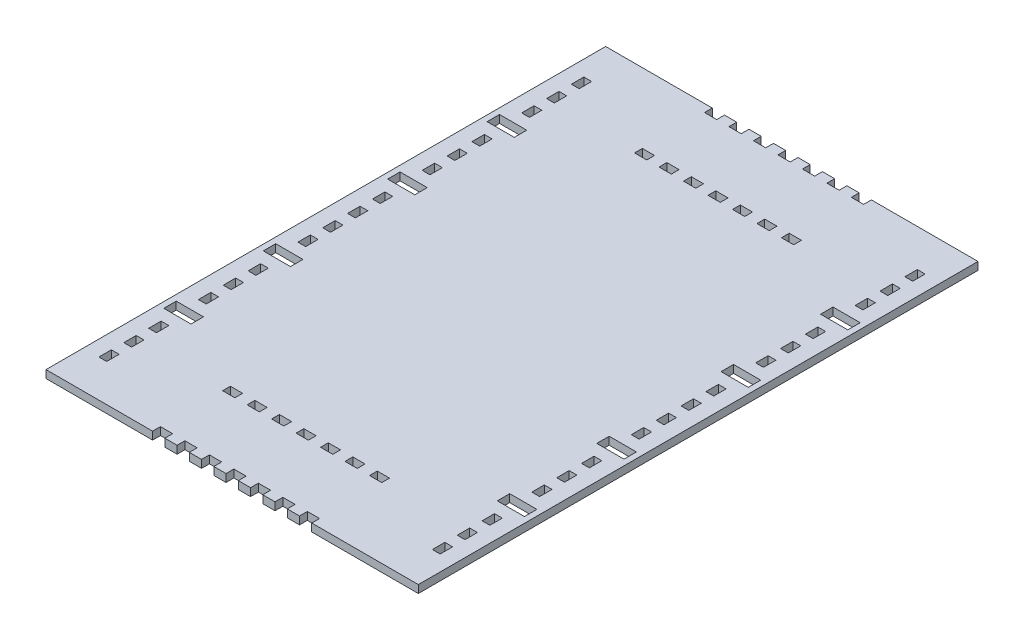
SolidWorks part; units mm, degrees
ref_plane "Front Plane" through (0, 0, 0) normal (0, 0, 1) x (1, 0, 0)
ref_plane "Top Plane" through (0, 0, 0) normal (0, 1, 0) x (1, 0, 0)
ref_plane "Right Plane" through (0, 0, 0) normal (1, 0, 0) x (0, 0, -1)
sketch "Sketch2" plane through (0, 0, 0) normal (0, 1, 0) x (1, 0, 0)
  line L0 (11.1148, -172.4341) -> (11.1148, -125.5432) construction
  line L1 (-64.9264, -175.6306) -> (-21.3852, -175.6306)
  line L2 (-64.9264, -175.6306) -> (-64.9264, -129.8959)
  line L3 (-64.9264, 52.9694) -> (-21.3852, 52.9694)
  line L4 (87.1561, -175.6306) -> (87.1561, -129.8959)
  line L5 (-58.5764, -160.3691) -> (-55.4014, -160.3691)
  line L6 (-58.5764, -160.3691) -> (-58.5764, -155.2891)
  line L7 (-58.5764, -155.2891) -> (-55.4014, -155.2891)
  line L8 (-55.4014, -160.3691) -> (-55.4014, -155.2891)
  line L9 (77.6311, -160.3691) -> (77.6311, -155.2891)
  line L10 (80.8061, -155.2891) -> (77.6311, -155.2891)
  line L11 (80.8061, -160.3691) -> (80.8061, -155.2891)
  line L12 (80.8061, -160.3691) -> (77.6311, -160.3691)
  line L13 (-58.5764, -150.2113) -> (-55.4014, -150.2113)
  line L14 (-58.5764, -150.2113) -> (-58.5764, -145.1313)
  line L15 (-58.5764, -145.1313) -> (-55.4014, -145.1313)
  line L16 (-55.4014, -150.2113) -> (-55.4014, -145.1313)
  line L17 (-58.5764, -140.0536) -> (-55.4014, -140.0536)
  line L18 (-58.5764, -140.0536) -> (-58.5764, -134.9736)
  line L19 (-58.5764, -134.9736) -> (-55.4014, -134.9736)
  line L20 (-55.4014, -140.0536) -> (-55.4014, -134.9736)
  line L21 (-58.5764, -160.3691) -> (-58.5764, -175.6306) construction
  line L22 (-64.9264, -84.1849) -> (-64.9264, -35.3087)
  line L23 (84.7748, -124.8159) -> (73.6623, -124.8159)
  line L24 (-64.9264, -33.3963) -> (-64.9264, -0.9698)
  line L25 (-58.5764, -119.7381) -> (-55.4014, -119.7381)
  line L26 (-58.5764, -119.7381) -> (-58.5764, -114.6581)
  line L27 (-58.5764, -114.6581) -> (-55.4014, -114.6581)
  line L28 (-55.4014, -119.7381) -> (-55.4014, -114.6581)
  line L29 (-58.5764, -109.5804) -> (-55.4014, -109.5804)
  line L30 (-58.5764, -109.5804) -> (-58.5764, -104.5004)
  line L31 (-58.5764, -104.5004) -> (-55.4014, -104.5004)
  line L32 (-55.4014, -109.5804) -> (-55.4014, -104.5004)
  line L33 (-58.5764, -99.4227) -> (-55.4014, -99.4227)
  line L34 (-58.5764, -99.4227) -> (-58.5764, -94.3427)
  line L35 (-58.5764, -94.3427) -> (-55.4014, -94.3427)
  line L36 (-55.4014, -99.4227) -> (-55.4014, -94.3427)
  line L37 (-58.5764, 37.7079) -> (-58.5764, 52.9694) construction
  line L38 (-64.9264, 7.2347) -> (-64.9264, 52.9694)
  line L39 (84.7748, -129.8959) -> (73.6623, -129.8959)
  line L40 (73.6623, -124.8159) -> (73.6623, -129.8959)
  line L41 (-58.5764, -79.1072) -> (-55.4014, -79.1072)
  line L42 (-58.5764, -79.1072) -> (-58.5764, -74.0272)
  line L43 (-58.5764, -74.0272) -> (-55.4014, -74.0272)
  line L44 (-55.4014, -79.1072) -> (-55.4014, -74.0272)
  line L45 (-58.5764, -68.9495) -> (-55.4014, -68.9495)
  line L46 (-58.5764, -68.9495) -> (-58.5764, -63.8695)
  line L47 (-58.5764, -63.8695) -> (-55.4014, -63.8695)
  line L48 (-55.4014, -68.9495) -> (-55.4014, -63.8695)
  line L49 (-58.5764, -58.7917) -> (-55.4014, -58.7917)
  line L50 (-58.5764, -58.7917) -> (-58.5764, -53.7117)
  line L51 (-58.5764, -53.7117) -> (-55.4014, -53.7117)
  line L52 (-55.4014, -58.7917) -> (-55.4014, -53.7117)
  line L53 (-58.5764, -48.634) -> (-55.4014, -48.634)
  line L54 (-58.5764, -48.634) -> (-58.5764, -43.554)
  line L55 (-58.5764, -43.554) -> (-55.4014, -43.554)
  line L56 (-55.4014, -48.634) -> (-55.4014, -43.554)
  line L57 (87.1561, -129.8959) -> (87.1561, -124.8159)
  line L58 (87.1561, -92.3894) -> (87.1561, -84.1849)
  line L59 (87.1561, -35.3087) -> (87.1561, -33.3963)
  line L60 (-64.9264, -129.8959) -> (-64.9264, -124.8159)
  line L61 (-58.5764, -28.3185) -> (-55.4014, -28.3185)
  line L62 (-58.5764, -28.3185) -> (-58.5764, -23.2385)
  line L63 (-58.5764, -23.2385) -> (-55.4014, -23.2385)
  line L64 (-55.4014, -28.3185) -> (-55.4014, -23.2385)
  line L65 (-58.5764, -18.1608) -> (-55.4014, -18.1608)
  line L66 (-58.5764, -18.1608) -> (-58.5764, -13.0808)
  line L67 (-58.5764, -13.0808) -> (-55.4014, -13.0808)
  line L68 (-55.4014, -18.1608) -> (-55.4014, -13.0808)
  line L69 (-58.5764, -8.0031) -> (-55.4014, -8.0031)
  line L70 (-58.5764, -8.0031) -> (-58.5764, -2.9231)
  line L71 (-58.5764, -2.9231) -> (-55.4014, -2.9231)
  line L72 (-55.4014, -8.0031) -> (-55.4014, -2.9231)
  line L73 (-64.9264, -92.3894) -> (-64.9264, -84.1849)
  line L74 (-64.9264, -35.3087) -> (-64.9264, -33.3963)
  line L75 (-64.9264, -0.9698) -> (-64.9264, 7.2347)
  line L76 (87.1561, -0.9698) -> (87.1561, 7.2347)
  line L77 (-58.5764, 12.3124) -> (-55.4014, 12.3124)
  line L78 (-58.5764, 12.3124) -> (-58.5764, 17.3924)
  line L79 (-58.5764, 17.3924) -> (-55.4014, 17.3924)
  line L80 (-55.4014, 12.3124) -> (-55.4014, 17.3924)
  line L81 (-58.5764, 22.4701) -> (-55.4014, 22.4701)
  line L82 (-58.5764, 22.4701) -> (-58.5764, 27.5501)
  line L83 (-58.5764, 27.5501) -> (-55.4014, 27.5501)
  line L84 (-55.4014, 22.4701) -> (-55.4014, 27.5501)
  line L85 (-58.5764, 32.6279) -> (-55.4014, 32.6279)
  line L86 (-58.5764, 32.6279) -> (-58.5764, 37.7079)
  line L87 (-58.5764, 37.7079) -> (-55.4014, 37.7079)
  line L88 (-55.4014, 32.6279) -> (-55.4014, 37.7079)
  line L89 (77.6311, 32.6279) -> (77.6311, 37.7079)
  line L90 (80.8061, 37.7079) -> (77.6311, 37.7079)
  line L91 (80.8061, 32.6279) -> (80.8061, 37.7079)
  line L92 (80.8061, 32.6279) -> (77.6311, 32.6279)
  line L93 (77.6311, 22.4701) -> (77.6311, 27.5501)
  line L94 (80.8061, 27.5501) -> (77.6311, 27.5501)
  line L95 (80.8061, 22.4701) -> (80.8061, 27.5501)
  line L96 (80.8061, 22.4701) -> (77.6311, 22.4701)
  line L97 (77.6311, 12.3124) -> (77.6311, 17.3924)
  line L98 (80.8061, 17.3924) -> (77.6311, 17.3924)
  line L99 (80.8061, 12.3124) -> (80.8061, 17.3924)
  line L100 (80.8061, 12.3124) -> (77.6311, 12.3124)
  line L101 (87.1561, -33.3963) -> (87.1561, -0.9698)
  line L102 (84.7748, -129.8959) -> (84.7748, -124.8159)
  line L103 (73.6623, -38.4763) -> (84.7748, -38.4763)
  line L104 (-62.5452, -129.8959) -> (-62.5452, -124.8159)
  line L105 (77.6311, -8.0031) -> (77.6311, -2.9231)
  line L106 (80.8061, -2.9231) -> (77.6311, -2.9231)
  line L107 (80.8061, -8.0031) -> (80.8061, -2.9231)
  line L108 (80.8061, -8.0031) -> (77.6311, -8.0031)
  line L109 (77.6311, -18.1608) -> (77.6311, -13.0808)
  line L110 (80.8061, -13.0808) -> (77.6311, -13.0808)
  line L111 (80.8061, -18.1608) -> (80.8061, -13.0808)
  line L112 (80.8061, -18.1608) -> (77.6311, -18.1608)
  line L113 (77.6311, -28.3185) -> (77.6311, -23.2385)
  line L114 (80.8061, -23.2385) -> (77.6311, -23.2385)
  line L115 (80.8061, -28.3185) -> (80.8061, -23.2385)
  line L116 (80.8061, -28.3185) -> (77.6311, -28.3185)
  line L117 (87.1561, -84.1849) -> (87.1561, -35.3087)
  line L118 (-62.5452, 2.1547) -> (-62.5452, 7.2347)
  line L119 (73.6623, -89.2649) -> (84.7748, -89.2649)
  line L120 (-62.5452, -38.4763) -> (-62.5452, -33.3963)
  line L121 (77.6311, -48.634) -> (77.6311, -43.554)
  line L122 (80.8061, -43.554) -> (77.6311, -43.554)
  line L123 (80.8061, -48.634) -> (80.8061, -43.554)
  line L124 (80.8061, -48.634) -> (77.6311, -48.634)
  line L125 (77.6311, -58.7917) -> (77.6311, -53.7117)
  line L126 (80.8061, -53.7117) -> (77.6311, -53.7117)
  line L127 (80.8061, -58.7917) -> (80.8061, -53.7117)
  line L128 (80.8061, -58.7917) -> (77.6311, -58.7917)
  line L129 (77.6311, -68.9495) -> (77.6311, -63.8695)
  line L130 (80.8061, -63.8695) -> (77.6311, -63.8695)
  line L131 (80.8061, -68.9495) -> (80.8061, -63.8695)
  line L132 (80.8061, -68.9495) -> (77.6311, -68.9495)
  line L133 (77.6311, -79.1072) -> (77.6311, -74.0272)
  line L134 (80.8061, -74.0272) -> (77.6311, -74.0272)
  line L135 (80.8061, -79.1072) -> (80.8061, -74.0272)
  line L136 (80.8061, -79.1072) -> (77.6311, -79.1072)
  line L137 (-64.9264, -124.8159) -> (-64.9264, -92.3894)
  line L138 (-62.5452, -89.2649) -> (-62.5452, -84.1849)
  line L139 (-51.4327, -124.8159) -> (-62.5452, -124.8159)
  line L140 (84.7748, -89.2649) -> (84.7748, -84.1849)
  line L141 (77.6311, -99.4227) -> (77.6311, -94.3427)
  line L142 (80.8061, -94.3427) -> (77.6311, -94.3427)
  line L143 (80.8061, -99.4227) -> (80.8061, -94.3427)
  line L144 (80.8061, -99.4227) -> (77.6311, -99.4227)
  line L145 (77.6311, -109.5804) -> (77.6311, -104.5004)
  line L146 (80.8061, -104.5004) -> (77.6311, -104.5004)
  line L147 (80.8061, -109.5804) -> (80.8061, -104.5004)
  line L148 (80.8061, -109.5804) -> (77.6311, -109.5804)
  line L149 (77.6311, -119.7381) -> (77.6311, -114.6581)
  line L150 (80.8061, -114.6581) -> (77.6311, -114.6581)
  line L151 (80.8061, -119.7381) -> (80.8061, -114.6581)
  line L152 (80.8061, -119.7381) -> (77.6311, -119.7381)
  line L153 (87.1561, 7.2347) -> (87.1561, 52.9694)
  line L154 (84.7748, -38.4763) -> (84.7748, -33.3963)
  line L155 (73.6623, 2.1547) -> (84.7748, 2.1547)
  line L156 (84.7748, 2.1547) -> (84.7748, 7.2347)
  line L157 (77.6311, -140.0536) -> (77.6311, -134.9736)
  line L158 (80.8061, -134.9736) -> (77.6311, -134.9736)
  line L159 (80.8061, -140.0536) -> (80.8061, -134.9736)
  line L160 (80.8061, -140.0536) -> (77.6311, -140.0536)
  line L161 (77.6311, -150.2113) -> (77.6311, -145.1313)
  line L162 (80.8061, -145.1313) -> (77.6311, -145.1313)
  line L163 (80.8061, -150.2113) -> (80.8061, -145.1313)
  line L164 (80.8061, -150.2113) -> (77.6311, -150.2113)
  line L165 (-21.3852, 52.9694) -> (-21.3852, 49.7944)
  line L166 (-21.3852, 49.7944) -> (-16.3852, 49.7944)
  line L167 (-16.3852, 49.7944) -> (-16.3852, 52.9694)
  line L168 (-11.3852, 52.9694) -> (-11.3852, 49.7944)
  line L169 (-11.3852, 49.7944) -> (-6.3852, 49.7944)
  line L170 (-6.3852, 49.7944) -> (-6.3852, 52.9694)
  line L171 (-1.3852, 52.9694) -> (-1.3852, 49.7944)
  line L172 (-1.3852, 49.7944) -> (3.6148, 49.7944)
  line L173 (3.6148, 49.7944) -> (3.6148, 52.9694)
  line L174 (8.6148, 52.9694) -> (8.6148, 49.7944)
  line L175 (8.6148, 49.7944) -> (13.6148, 49.7944)
  line L176 (13.6148, 49.7944) -> (13.6148, 52.9694)
  line L177 (18.6148, 52.9694) -> (18.6148, 49.7944)
  line L178 (18.6148, 49.7944) -> (23.6148, 49.7944)
  line L179 (23.6148, 49.7944) -> (23.6148, 52.9694)
  line L180 (28.6148, 52.9694) -> (28.6148, 49.7944)
  line L181 (28.6148, 49.7944) -> (33.6148, 49.7944)
  line L182 (33.6148, 49.7944) -> (33.6148, 52.9694)
  line L183 (38.6148, 52.9694) -> (38.6148, 49.7944)
  line L184 (38.6148, 49.7944) -> (43.6148, 49.7944)
  line L185 (43.6148, 49.7944) -> (43.6148, 52.9694)
  line L186 (-16.3852, 52.9694) -> (-11.3852, 52.9694) construction
  line L187 (-16.3852, 52.9694) -> (-11.3852, 52.9694)
  line L188 (3.6148, 52.9694) -> (8.6148, 52.9694)
  line L189 (-6.3852, 52.9694) -> (-1.3852, 52.9694)
  line L190 (13.6148, 52.9694) -> (18.6148, 52.9694)
  line L191 (23.6148, 52.9694) -> (28.6148, 52.9694)
  line L192 (33.6148, 52.9694) -> (38.6148, 52.9694)
  line L193 (43.6148, 52.9694) -> (87.1561, 52.9694)
  line L194 (-21.3754, 24.3944) -> (-21.3754, 21.2194)
  line L195 (-21.3754, 21.2194) -> (-16.3754, 21.2194)
  line L196 (-16.3754, 21.2194) -> (-16.3754, 24.3944)
  line L197 (-11.3754, 24.3944) -> (-11.3754, 21.2194)
  line L198 (-11.3754, 21.2194) -> (-6.3754, 21.2194)
  line L199 (-6.3754, 21.2194) -> (-6.3754, 24.3944)
  line L200 (-1.3754, 24.3944) -> (-1.3754, 21.2194)
  line L201 (-1.3754, 21.2194) -> (3.6246, 21.2194)
  line L202 (3.6246, 21.2194) -> (3.6246, 24.3944)
  line L203 (8.6246, 24.3944) -> (8.6246, 21.2194)
  line L204 (8.6246, 21.2194) -> (13.6246, 21.2194)
  line L205 (13.6246, 21.2194) -> (13.6246, 24.3944)
  line L206 (18.6246, 24.3944) -> (18.6246, 21.2194)
  line L207 (18.6246, 21.2194) -> (23.6246, 21.2194)
  line L208 (23.6246, 21.2194) -> (23.6246, 24.3944)
  line L209 (28.6246, 24.3944) -> (28.6246, 21.2194)
  line L210 (28.6246, 21.2194) -> (33.6246, 21.2194)
  line L211 (33.6246, 21.2194) -> (33.6246, 24.3944)
  line L212 (38.6246, 24.3944) -> (38.6246, 21.2194)
  line L213 (38.6246, 21.2194) -> (43.6246, 21.2194)
  line L214 (43.6246, 21.2194) -> (43.6246, 24.3944)
  line L215 (-21.3754, 24.3944) -> (-16.3754, 24.3944)
  line L216 (-11.3754, 24.3944) -> (-6.3754, 24.3944)
  line L217 (-1.3754, 24.3944) -> (3.6246, 24.3944)
  line L218 (8.6246, 24.3944) -> (13.6246, 24.3944)
  line L219 (18.6246, 24.3944) -> (23.6246, 24.3944)
  line L220 (28.6246, 24.3944) -> (33.6246, 24.3944)
  line L221 (38.6246, 24.3944) -> (43.6246, 24.3944)
  line L222 (-16.3754, 24.3944) -> (-11.3754, 24.3944) [skipped]
  line L223 (-16.3754, 24.3944) -> (-11.3754, 24.3944) construction
  line L224 (-6.3754, 24.3944) -> (-1.3754, 24.3944) [skipped]
  line L225 (3.6246, 24.3944) -> (8.6246, 24.3944) [skipped]
  line L226 (13.6246, 24.3944) -> (18.6246, 24.3944) [skipped]
  line L227 (23.6246, 24.3944) -> (28.6246, 24.3944) [skipped]
  line L228 (33.6246, 24.3944) -> (38.6246, 24.3944) [skipped]
  line L229 (-64.9264, -63.8491) -> (87.1561, -63.8491) construction
  line L230 (-16.3852, -175.6306) -> (-11.3852, -175.6306)
  line L231 (38.6148, -147.0341) -> (43.6148, -147.0341)
  line L232 (28.6148, -147.0341) -> (33.6148, -147.0341)
  line L233 (18.6148, -147.0341) -> (23.6148, -147.0341)
  line L234 (8.6148, -147.0341) -> (13.6148, -147.0341)
  line L235 (-1.3852, -147.0341) -> (3.6148, -147.0341)
  line L236 (-11.3852, -147.0341) -> (-6.3852, -147.0341)
  line L237 (-21.3852, -147.0341) -> (-16.3852, -147.0341)
  line L238 (43.6148, -143.8591) -> (43.6148, -147.0341)
  line L239 (38.6148, -143.8591) -> (43.6148, -143.8591)
  line L240 (38.6148, -147.0341) -> (38.6148, -143.8591)
  line L241 (33.6148, -143.8591) -> (33.6148, -147.0341)
  line L242 (28.6148, -143.8591) -> (33.6148, -143.8591)
  line L243 (28.6148, -147.0341) -> (28.6148, -143.8591)
  line L244 (23.6148, -143.8591) -> (23.6148, -147.0341)
  line L245 (18.6148, -143.8591) -> (23.6148, -143.8591)
  line L246 (18.6148, -147.0341) -> (18.6148, -143.8591)
  line L247 (13.6148, -143.8591) -> (13.6148, -147.0341)
  line L248 (8.6148, -143.8591) -> (13.6148, -143.8591)
  line L249 (8.6148, -147.0341) -> (8.6148, -143.8591)
  line L250 (3.6148, -143.8591) -> (3.6148, -147.0341)
  line L251 (-1.3852, -143.8591) -> (3.6148, -143.8591)
  line L252 (-1.3852, -147.0341) -> (-1.3852, -143.8591)
  line L253 (-6.3852, -143.8591) -> (-6.3852, -147.0341)
  line L254 (-11.3852, -143.8591) -> (-6.3852, -143.8591)
  line L255 (-11.3852, -147.0341) -> (-11.3852, -143.8591)
  line L256 (-16.3852, -143.8591) -> (-16.3852, -147.0341)
  line L257 (-21.3852, -143.8591) -> (-16.3852, -143.8591)
  line L258 (-21.3852, -147.0341) -> (-21.3852, -143.8591)
  line L259 (-6.3852, -175.6306) -> (-1.3852, -175.6306)
  line L260 (3.6148, -175.6306) -> (8.6148, -175.6306)
  line L261 (13.6148, -175.6306) -> (18.6148, -175.6306)
  line L262 (23.6148, -175.6306) -> (28.6148, -175.6306)
  line L263 (33.6148, -175.6306) -> (38.6148, -175.6306)
  line L264 (84.7748, -84.1849) -> (87.1561, -84.1849) construction
  line L265 (43.6148, -175.6306) -> (43.6148, -172.4341)
  line L266 (38.6148, -172.4341) -> (43.6148, -172.4341)
  line L267 (38.6148, -175.6306) -> (38.6148, -172.4341)
  line L268 (33.6148, -175.6306) -> (33.6148, -172.4341)
  line L269 (28.6148, -172.4341) -> (33.6148, -172.4341)
  line L270 (28.6148, -175.6306) -> (28.6148, -172.4341)
  line L271 (23.6148, -175.6306) -> (23.6148, -172.4341)
  line L272 (18.6148, -172.4341) -> (23.6148, -172.4341)
  line L273 (18.6148, -175.6306) -> (18.6148, -172.4341)
  line L274 (13.6148, -175.6306) -> (13.6148, -172.4341)
  line L275 (8.6148, -172.4341) -> (13.6148, -172.4341)
  line L276 (8.6148, -175.6306) -> (8.6148, -172.4341)
  line L277 (3.6148, -175.6306) -> (3.6148, -172.4341)
  line L278 (-1.3852, -172.4341) -> (3.6148, -172.4341)
  line L279 (-1.3852, -175.6306) -> (-1.3852, -172.4341)
  line L280 (-6.3852, -175.6306) -> (-6.3852, -172.4341)
  line L281 (-11.3852, -172.4341) -> (-6.3852, -172.4341)
  line L282 (-11.3852, -175.6306) -> (-11.3852, -172.4341)
  line L283 (-16.3852, -175.6306) -> (-16.3852, -172.4341)
  line L284 (-21.3852, -172.4341) -> (-16.3852, -172.4341)
  line L285 (-21.3852, -175.6306) -> (-21.3852, -172.4341)
  line L286 (84.7748, -124.8159) -> (87.1561, -124.8159) construction
  line L287 (84.7748, -33.3963) -> (87.1561, -33.3963) construction
  line L288 (84.7748, 7.2347) -> (87.1561, 7.2347) construction
  line L289 (-64.9264, 7.2347) -> (-62.5452, 7.2347) construction
  line L290 (87.1561, -124.8159) -> (87.1561, -92.3894)
  line L291 (43.6148, -175.6306) -> (87.1561, -175.6306)
  line L292 (73.6623, 2.1547) -> (73.6623, 7.2347)
  line L293 (73.6623, 7.2347) -> (84.7748, 7.2347)
  line L294 (73.6623, -38.4763) -> (73.6623, -33.3963)
  line L295 (73.6623, -33.3963) -> (84.7748, -33.3963)
  line L296 (73.6623, -89.2649) -> (73.6623, -84.1849)
  line L297 (73.6623, -84.1849) -> (84.7748, -84.1849)
  line L298 (-51.4327, -124.8159) -> (-51.4327, -129.8959)
  line L299 (-51.4327, -129.8959) -> (-55.4014, -129.8959)
  line L300 (-62.5452, 7.2347) -> (-62.4518, 7.3491) construction
  line L301 (-51.4327, -84.1849) -> (-62.5452, -84.1849)
  line L302 (-51.4327, -84.1849) -> (-51.4327, -89.2649)
  line L303 (-51.4327, -89.2649) -> (-62.5452, -89.2649)
  line L304 (-64.9264, -33.3963) -> (-62.5452, -33.3963) construction
  line L305 (-51.4327, -33.3963) -> (-62.5452, -33.3963)
  line L306 (-51.4327, -33.3963) -> (-51.4327, -38.4763)
  line L307 (-51.4327, -38.4763) -> (-62.5452, -38.4763)
  line L308 (-64.9264, -124.8159) -> (-62.5452, -124.8159) construction
  line L309 (-51.4327, 7.2347) -> (-62.5452, 7.2347)
  line L310 (-51.4327, 7.2347) -> (-51.4327, 2.1547)
  line L311 (-51.4327, 2.1547) -> (-62.5452, 2.1547)
  line L312 (-64.9264, -84.1849) -> (-62.5452, -84.1849) construction
  line L313 (-55.4014, -129.8959) -> (-55.4014, -124.8159) [skipped]
  line L314 (-58.5764, -129.8959) -> (-58.5764, -124.8159) [skipped]
  line L315 (-55.4014, -89.2649) -> (-55.4014, -84.1849) [skipped]
  line L316 (-58.5764, -89.2649) -> (-58.5764, -84.1849) [skipped]
  line L317 (-55.4014, -38.4763) -> (-55.4014, -33.3963) [skipped]
  line L318 (-58.5764, -38.4763) -> (-58.5764, -33.3963) [skipped]
  line L319 (-55.4014, 2.1547) -> (-55.4014, 7.2347) [skipped]
  line L320 (-58.5764, 2.1547) -> (-58.5764, 7.2347) [skipped]
  line L321 (-58.5764, -129.8959) -> (-55.4014, -129.8959) [skipped]
  line L322 (-58.5764, -124.8159) -> (-55.4014, -124.8159) [skipped]
  line L323 (-58.5764, -89.2649) -> (-55.4014, -89.2649) [skipped]
  line L324 (-58.5764, -84.1849) -> (-55.4014, -84.1849) [skipped]
  line L325 (-58.5764, -38.4763) -> (-55.4014, -38.4763) [skipped]
  line L326 (-58.5764, -33.3963) -> (-55.4014, -33.3963) [skipped]
  line L327 (-58.5764, 2.1547) -> (-55.4014, 2.1547) [skipped]
  line L328 (-58.5764, 7.2347) -> (-55.4014, 7.2347) [skipped]
  line L329 (-58.5764, -134.9736) -> (-58.5764, -129.8959) construction
  line L330 (-55.4014, -134.9736) -> (-55.4014, -129.8959) construction
  line L331 (-58.5764, -129.8959) -> (-62.5452, -129.8959)
  line L332 (-58.5764, -129.8959) -> (-55.4014, -129.8959)
  line L333 (-58.5764, -94.3427) -> (-58.5764, -89.2649) construction
  line L334 (-58.5764, -43.554) -> (-58.5764, -38.4763) construction
  line L335 (-58.5764, -2.9231) -> (-58.5764, 2.1547) construction
  line L336 (80.8061, -2.9231) -> (80.8061, 2.1547) construction
  line L337 (80.8061, -43.554) -> (80.8061, -38.4763) construction
  line L338 (80.8061, -94.3427) -> (80.8061, -89.2649) construction
  line L339 (80.8061, -134.9736) -> (80.8061, -129.8959) construction
  line L340 (-58.5764, 12.3124) -> (-58.5764, 7.2347) construction
  line L341 (-17.1489, 24.3944) -> (-17.1489, 40.2694) construction
  line L342 (-17.1489, 40.2694) -> (-17.1489, 43.4444) construction
  dimension "D1" = 152.0825
  dimension "D2" = 6.35
  dimension "D3" = 6.35
  dimension "D4" = 3.175
  dimension "D5" = 5.08
  dimension "D6" = 3.175
  dimension "D8" = 228.6
  dimension "D9" = 5
  dimension "D10" = 10
  dimension "D11" = 2
  dimension "D12" = 7
  dimension "D13" = 25.4
  dimension "D14" = 11.1125
  dimension "D15" = 5.08
  dimension "D16" = 25.4
  dimension "D17" = 3.175
  dimension "D18" = 5
  dimension "D19" = 5
  dimension "D21" = 5
  dimension "D22" = 5
  dimension "D7" = 20
extrude "Boss-Extrude1" add sketch "Sketch2" along normal blind 3.175
sketch "Sketch4" plane through (0, 0, 0) normal (0, -1, 0) x (1, 0, 0)
sketch "Sketch3" plane through (0, 0, 0) normal (0, -1, 0) x (-1, 0, 0)
